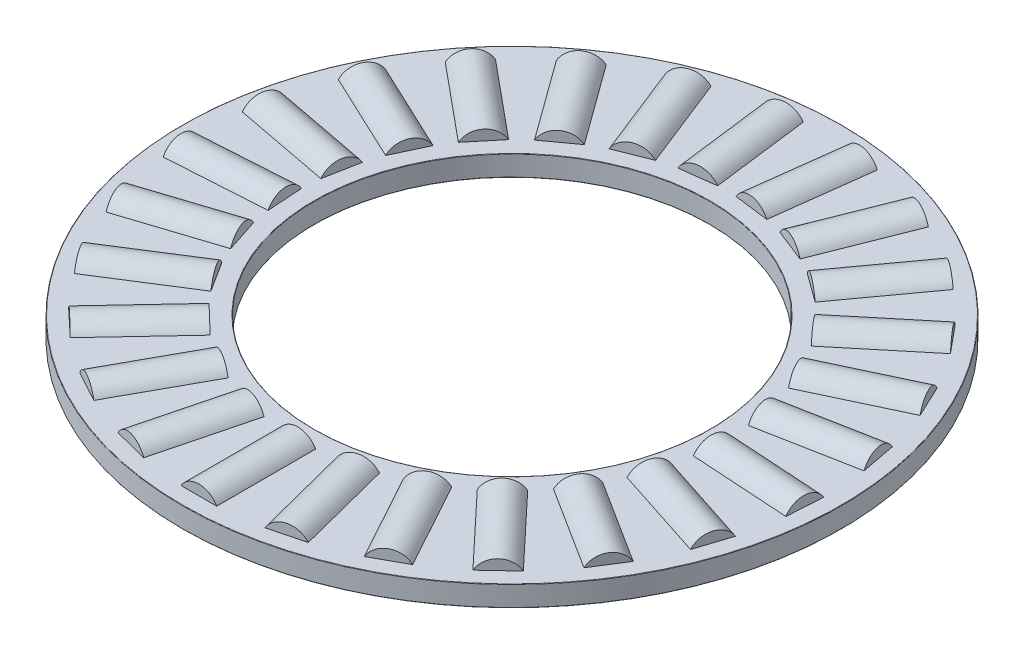
SolidWorks part; units mm, degrees
ref_plane "Front Plane" through (0, 0, 0) normal (0, 0, 1) x (1, 0, 0)
ref_plane "Top Plane" through (0, 0, 0) normal (0, 1, 0) x (1, 0, 0)
ref_plane "Right Plane" through (0, 0, 0) normal (1, 0, 0) x (0, 0, -1)
sketch "Sketch1" plane through (0, 0, 0) normal (1, 0, 0) x (0, 0, -1)
  line L0 (-15.875, 0) -> (15.875, 0) construction
  line L1 (0, -0.9922) -> (0, 0.9922) construction
  line L2 (-15.875, 0.4961) -> (-9.525, 0.4961)
  line L3 (-15.875, 0.4961) -> (-15.875, -0.4961)
  line L4 (-15.875, -0.4961) -> (-9.525, -0.4961)
  line L5 (-9.525, 0.4961) -> (-9.525, -0.4961)
  line L7 (-12.7, 0.9922) -> (-12.7, 0.4961) construction
  line L8 (-15.0813, 0.9922) -> (-10.3188, 0.9922) construction
  line L9 (-15.0813, 0.9922) -> (-15.0813, -0.9922) construction
  line L10 (-15.0813, -0.9922) -> (-10.3188, -0.9922) construction
  line L11 (-10.3188, 0.9922) -> (-10.3188, -0.9922) construction
  point P16 (-15.0813, 0)
revolve "Revolve1" add sketch "Sketch1" angle 360 about L1
sketch "Sketch3" plane through (0, 0, 0) normal (1, 0, 0) x (0, 0, -1)
  line L0 (-15.0813, 0.9922) -> (-15.0813, -0.9922) construction
  line L1 (-15.0813, 0) -> (-10.3188, 0)
  line L2 (-15.0813, 0) -> (-15.0813, 0.9922)
  line L3 (-15.0813, 0.9922) -> (-10.3188, 0.9922)
  line L4 (-10.3188, 0) -> (-10.3188, 0.9922)
revolve "Cut-Revolve1" cut sketch "Sketch3" angle 360 about L1
sketch "Sketch2" plane through (0, 0, 0) normal (1, 0, 0) x (0, 0, -1)
  line L1 (-15.0813, 0) -> (-10.3188, 0)
  line L2 (-15.0813, 0) -> (-15.0813, 0.9922)
  line L3 (-15.0813, 0.9922) -> (-10.3188, 0.9922)
  line L4 (-10.3188, 0) -> (-10.3188, 0.9922)
revolve "Revolve2" add sketch "Sketch2" angle 360 about L1
ref_axis "Axis1" through (0, 0.9922, 0) along (0, -1, 0)
pattern_circular "CirPattern1" count 25 every 14.4 about axis through (0, 0.9922, 0) along (0, -1, 0) of bodies 187 411
pattern_circular "CirPattern2" count 25 every 14.4 about axis through (0, 0, 0) along (0, 1, 0) of "Cut-Revolve1"
sketch "Sketch4" plane through (0, 0, 0) normal (1, 0, 0) x (0, 0, -1)
  line L0 (-15.875, 0.4961) -> (-15.875, -0.4961) construction
  line L1 (-15.875, 9.1091) -> (-9.525, 9.1091)
  line L2 (-15.875, 9.1091) -> (-15.875, 9.9219)
  line L3 (-15.875, 9.9219) -> (-9.525, 9.9219)
  line L4 (-9.525, 9.1091) -> (-9.525, 9.9219)
  line L5 (-15.875, -9.9219) -> (-9.525, -9.9219)
  line L6 (-15.875, -9.9219) -> (-15.875, -9.1091)
  line L7 (-15.875, -9.1091) -> (-9.525, -9.1091)
  line L8 (-9.525, -9.9219) -> (-9.525, -9.1091)
  line L10 (-9.525, 0.4961) -> (-9.525, -0.4961) construction
  line L11 (0, 0) -> (-15.875, 0) construction
  line L12 (-15.875, 0) -> (15.875, 0) construction
  line L13 (0, -0.9922) -> (0, 0.9922) construction
revolve "Revolve3" [suppressed] add sketch "Sketch4" angle 360 about L1
fillet "Fillet1" [suppressed] radius 0.0198
fillet "Fillet2" radius 0.0198 4 edges at (0, -0.4961, -9.525) (0, 0.4961, -9.525) (0, -0.4961, -15.875) (0, 0.4961, -15.875)
fillet "Fillet3" [suppressed] radius 0.0198
equation "\"D2@Sketch1\" = \"Th@Sketch1\"*.5"
equation "\"D1@Fillet1\" = \"Th@Sketch1\"*.01"
equation "\"D1@Fillet2\" = \"D1@Fillet1\""
equation "\"D1@Fillet3\" = \"D1@Fillet1\""
equation "\"D1@Sketch1\" = \"D3@Sketch1\"*.75"
equation "\"Angle@CirPattern1\" = 360/\"Rollers@CirPattern1\""
equation "\"Rollers@CirPattern1\" = \"OD@Sketch1\"*20"
equation "\"D1@CirPattern2\" = \"Rollers@CirPattern1\""
equation "\"D2@CirPattern2\" = \"Angle@CirPattern1\""
equation "\"Ht@Sketch4\" = \"Th@Sketch1\"*10"
